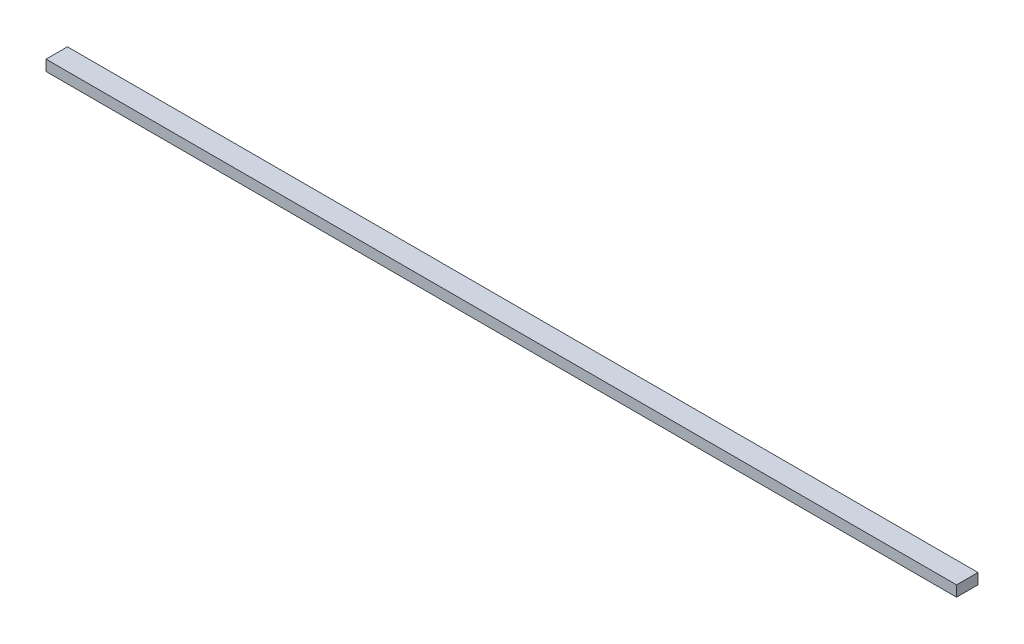
SolidWorks part; units mm, degrees
ref_plane "Alzado" through (0, 0, 0) normal (0, 0, 1) x (1, 0, 0)
ref_plane "Planta" through (0, 0, 0) normal (0, 1, 0) x (1, 0, 0)
ref_plane "Vista lateral" through (0, 0, 0) normal (1, 0, 0) x (0, 0, -1)
sketch "Croquis1" plane through (0, 0, 0) normal (0, 0, 1) x (1, 0, 0)
  line L1 (-158.253, 28.0585) -> (3241.747, 28.0585)
  line L2 (-158.253, 28.0585) -> (-158.253, -11.9415)
  line L3 (-158.253, -11.9415) -> (3241.747, -11.9415)
  line L4 (3241.747, 28.0585) -> (3241.747, -11.9415)
extrude "Saliente-Extruir1" add sketch "Croquis1" along normal blind 80
sketch "Croquis2" plane through (-158.253, 0, 0) normal (-1, 0, 0) x (0, 0, 1)
  line L1 (5.8286, 23.0811) -> (76.5555, 23.0811)
  line L2 (5.8286, 23.0811) -> (5.8286, -7.755)
  line L3 (5.8286, -7.755) -> (76.5555, -7.755)
  line L4 (76.5555, 23.0811) -> (76.5555, -7.755)
extrude "Saliente-Extruir2" add sketch "Croquis2" against normal blind 3400
sketch "Croquis3" plane through (3241.747, 0, 0) normal (1, 0, 0) x (0, 0, -1)
  line L1 (-70.0479, 19.9134) -> (-7.9031, 19.9134)
  line L2 (-70.0479, 19.9134) -> (-70.0479, -6.8253)
  line L3 (-70.0479, -6.8253) -> (-7.9031, -6.8253)
  line L4 (-7.9031, 19.9134) -> (-7.9031, -6.8253)
sketch "Croquis4" plane through (3241.747, 0, 0) normal (1, 0, 0) x (0, 0, -1)
extrude "Saliente-Extruir4" add sketch "Croquis3" against normal blind 3400
sketch "Croquis6" plane through (3241.747, 0, 0) normal (1, 0, 0) x (0, 0, -1)
  line L1 (-77.1488, 25.661) -> (-2.9039, 25.661)
  line L2 (-77.1488, 25.661) -> (-77.1488, -9.8044)
  line L3 (-77.1488, -9.8044) -> (-2.9039, -9.8044)
  line L4 (-2.9039, 25.661) -> (-2.9039, -9.8044)
